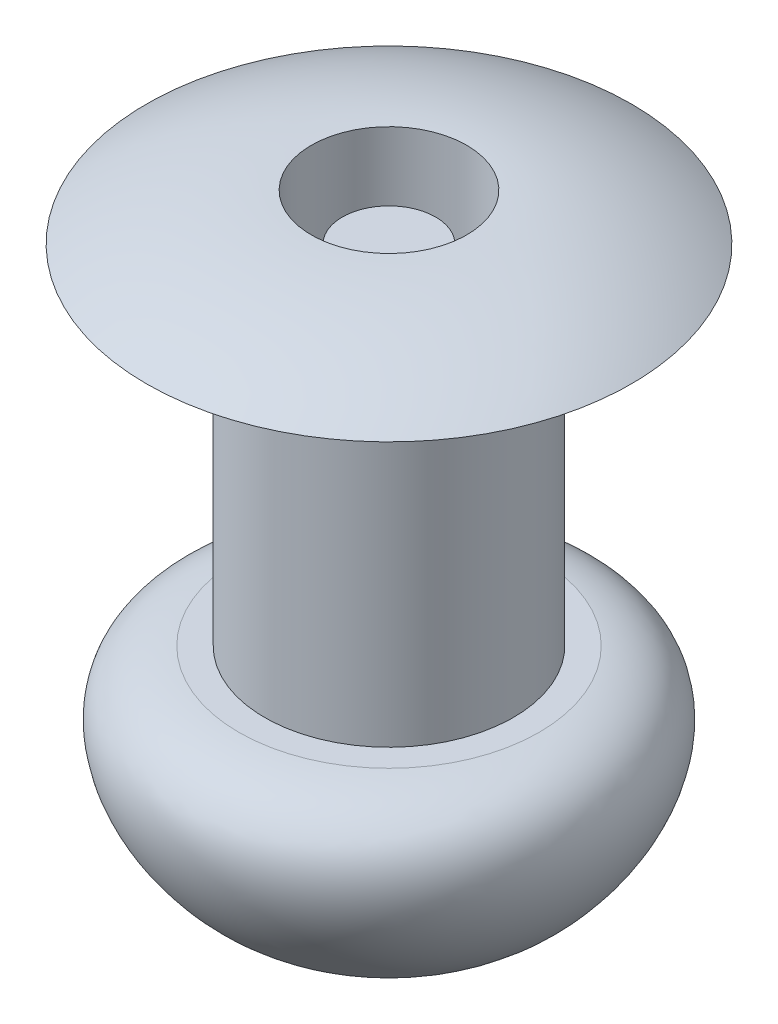
SolidWorks part; units mm, degrees
material "AISI 316 Stal nierdzewna odprężona (SS)"
ref_plane "Płaszczyzna przednia" through (0, 0, 0) normal (0, 0, 1) x (1, 0, 0)
ref_plane "Płaszczyzna górna" through (0, 0, 0) normal (0, 1, 0) x (1, 0, 0)
ref_plane "Płaszczyzna prawa" through (0, 0, 0) normal (1, 0, 0) x (0, 0, -1)
sketch "Szkic1" plane through (0, 0, 0) normal (1, 0, 0) x (0, 0, -1)
  line L0 (0, 0) -> (0, -4.1217)
  line L1 (0, 0) -> (-0.75, 0)
  line L2 (-0.75, 0) -> (-0.75, -5.7984)
  line L3 (-0.75, -5.7984) -> (-1.25, -5.7984)
  line L4 (-1.25, -5.7984) -> (-1.25, 0.75)
  line L5 (-3.9, 0) -> (-2, 0)
  line L6 (-2, 0) -> (-2, -5.5977)
  line L7 (-2, -5.5977) -> (-2.4139, -5.5977)
  line L8 (0, 0) -> (0, 0.4842) construction
  line L9 (0, -5.7984) -> (0, -4.1217)
  line L10 (0, -5.7984) -> (0, -7.2984)
  arc A0 (-1.25, 0.75) -> (-3.9, 0) centre (-1.25, -4.3067) ccw
  ellipse E0 centre (0, -6.5484) end of major axis (-1.75, -6.5484) minor radius 0.75 (-0.956, -7.1766) -> (0, -7.2984) ccw
  spline S0 degree 3 poles (-2.4139, -5.5977) (-3.8675, -5.7674) (-3.5289, -7.8997) (-1.084, -9.4712) (-0.2718, -7.4726) (-0.956, -7.1766) knots 0 0 0 0 0.464993 0.721928 1 1 1 1
  dimension "D1" = 7.8
  dimension "D2" = 2.5
  dimension "D3" = 4
  dimension "D4" = 0.75
  dimension "D5" = 1.5
  dimension "D6" = 1.5
  dimension "D7" = 3.5
  dimension "D8" = 3.1855
  dimension "D9" = 2.5026
  dimension "D10" = 1.9
  dimension "D11" = 1.5789
  dimension "D12" = 0.5792
  dimension "D13" = 4.8278
  dimension "D14" = 3.3858
  dimension "D15" = 2.8395
  dimension "D16" = 1.25
  dimension "D17" = 0.6409
  dimension "D18" = 0.956
revolve "Obrót1" add sketch "Szkic1" angle 360 about L8
